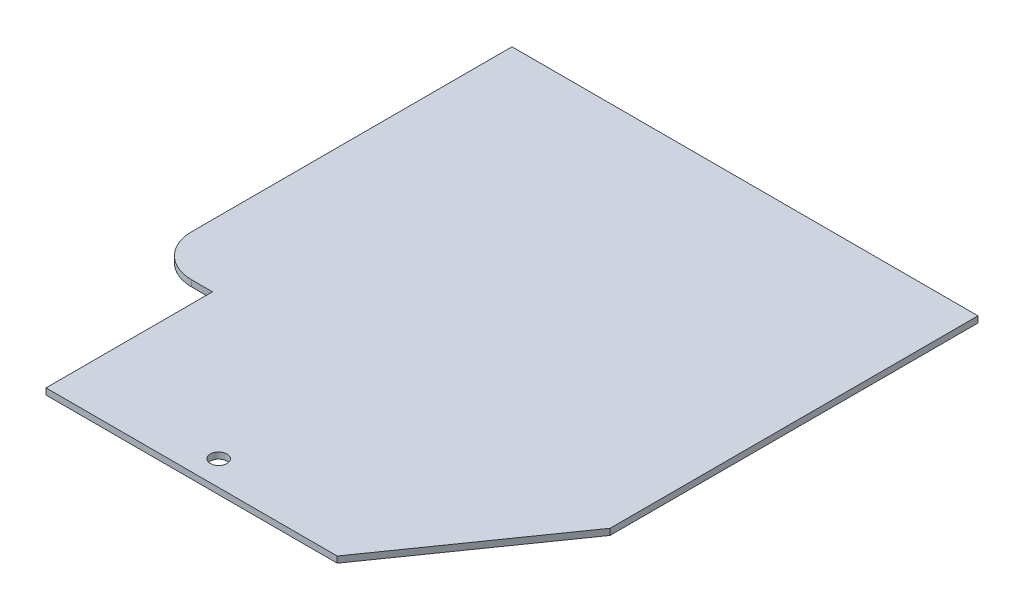
SolidWorks part; units mm, degrees
ref_plane "Ön Düzlem" through (0, 0, 0) normal (0, 0, 1) x (1, 0, 0)
ref_plane "Üst Düzlem" through (0, 0, 0) normal (0, 1, 0) x (1, 0, 0)
ref_plane "Sağ Düzlem" through (0, 0, 0) normal (1, 0, 0) x (0, 0, -1)
sketch "Çizim15" plane through (0, 0, 0) normal (0, 1, 0) x (1, 0, 0)
  line L0 (0, 0) -> (70, 0)
  line L1 (70, 0) -> (97.0083, 38.5719)
  line L8 (0, 0) -> (0, 40)
  line L9 (0, 40) -> (-5, 40)
  line L10 (-15, 50) -> (-15, 55)
  line L15 (-15, 55) -> (-15, 127)
  line L16 (-15, 127) -> (97.0083, 127)
  line L19 (97.0083, 127) -> (97.0083, 38.5719)
  arc A0 (-5, 40) -> (-15, 50) centre (-5, 50) cw
  circle A1 centre (35.5, 6) radius 2
  dimension "D1" = 10
extrude "Yükseklik-Ekstrüzyon1" add sketch "Çizim15" along normal blind 1.5
